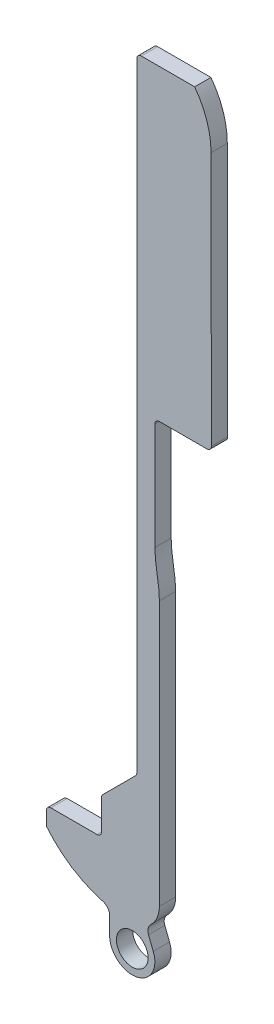
SolidWorks part; units mm, degrees
ref_plane "Płaszczyzna przednia" through (0, 0, 0) normal (0, 0, 1) x (1, 0, 0)
ref_plane "Płaszczyzna górna" through (0, 0, 0) normal (0, 1, 0) x (1, 0, 0)
ref_plane "Płaszczyzna prawa" through (0, 0, 0) normal (1, 0, 0) x (0, 0, -1)
sketch "Sketch1" plane through (0, 0, 0) normal (0, 0, 1) x (1, 0, 0)
  line L0 (0, 4.5) -> (0, 6.5)
  line L1 (0, 0) -> (18.25, 0) construction
  line L2 (0, 0) -> (0, 83.5) construction
  line L3 (0, 83.5) -> (18.25, 83.5) construction
  line L4 (18.25, 0) -> (18.25, 83.5) construction
  line L5 (0, 6.5) -> (6.1, 6.5)
  line L6 (6.1, 6.5) -> (6.1, 10.5)
  line L7 (6.1, 10.5) -> (10, 14.4)
  line L8 (10, 14.4) -> (10, 83.5)
  line L9 (10, 83.5) -> (16.4, 83.5)
  line L10 (18.2123, 78.0955) -> (18.25, 49.5)
  line L11 (18.25, 49.5) -> (12, 49.5)
  line L12 (12, 49.5) -> (12, 37.18)
  line L13 (12, 35.24) -> (12, 39.1406) construction
  line L14 (12.5, 32.33) -> (12.5, 3.07)
  line L15 (12.5, 31.0162) -> (12.5, 33.6438) construction
  arc A0 (16.4, 83.5) -> (18.2123, 78.0955) centre (9.2123, 78.0836) cw
  arc A1 (12.5, 3.07) -> (9.43, 0) centre (9.43, 3.07) cw
  arc A2 (9.43, 0) -> (0, 4.5) centre (9.43, 12.1305) cw
  spline S0 degree 3 poles (12, 37.18) (12, 35.5548) (12.5, 33.9723) (12.5, 32.33) knots 0 0 0 0 1 1 1 1
  point P5 (16.4, 83.5)
  point P6 (0, 6.5)
  point P7 (0, 4.5)
  point P8 (18.25, 49.5)
  dimension "D11" = 9
  dimension "D1" = 83.5
  dimension "D2" = 18.25
  dimension "D3" = 1.85
  dimension "D4" = 34
  dimension "D5" = 4.5
  dimension "D6" = 2
  dimension "D7" = 6.1
  dimension "D8" = 4
  dimension "D9" = 45
  dimension "D10" = 3.9
  dimension "D12" = 6.25
  dimension "D13" = 12.32
  dimension "D14" = 29.26
  dimension "D15" = 4.85
extrude "Boss-Extrude1" add sketch "Sketch1" along normal blind 1.8
fillet "Fillet1" radius 0.5 7 edges at (0, 6.5, 0.9) (6.1, 6.5, 0.9) (6.1, 10.5, 0.9) (10, 14.4, 0.9) (18.25, 49.5, 0.9) (10, 83.5, 0.9) (12, 49.5, 0.9)
sketch "Sketch5" plane through (0, 0, 0) normal (0, 0, -1) x (-1, 0, 0)
  line L0 (-12.5, 3.07) -> (-12.5, 32.33) construction
  line L1 (-7, -2.4998) -> (-7, 0.5002)
  line L2 (-7, 0.5002) -> (-11, 0.5002)
  line L3 (-11, 0.5002) -> (-11.824, -1.5785)
  circle A0 centre (-9.5, -2.4998) radius 2.5
  arc A1 (-9.43, 0) -> (0, 4.5) centre (-9.43, 12.1305) ccw construction
  circle A2 centre (-9.5, -2.4998) radius 1.75
  arc M20 (-12.5, 3.07) -> (-9.43, 0) centre (-9.43, 3.07) ccw
  arc M21 (-9.43, 0) -> (0, 4.5) centre (-9.43, 12.1305) ccw
  dimension "D1" = 5
  dimension "D5" = 3.5
  dimension "D2" = 3
  dimension "D3" = 3
  dimension "D4" = 4
extrude "Boss-Extrude2" add sketch "Sketch5" against normal blind 1.8 contours A0 A2 | A0 L1 L3 M21 M20 | L2 L3 L1 M20 M21
fillet "Fillet2" radius 1 2 edges at (7, 0.2459, 0.9) (11.0219, 0.445, 0.9)
